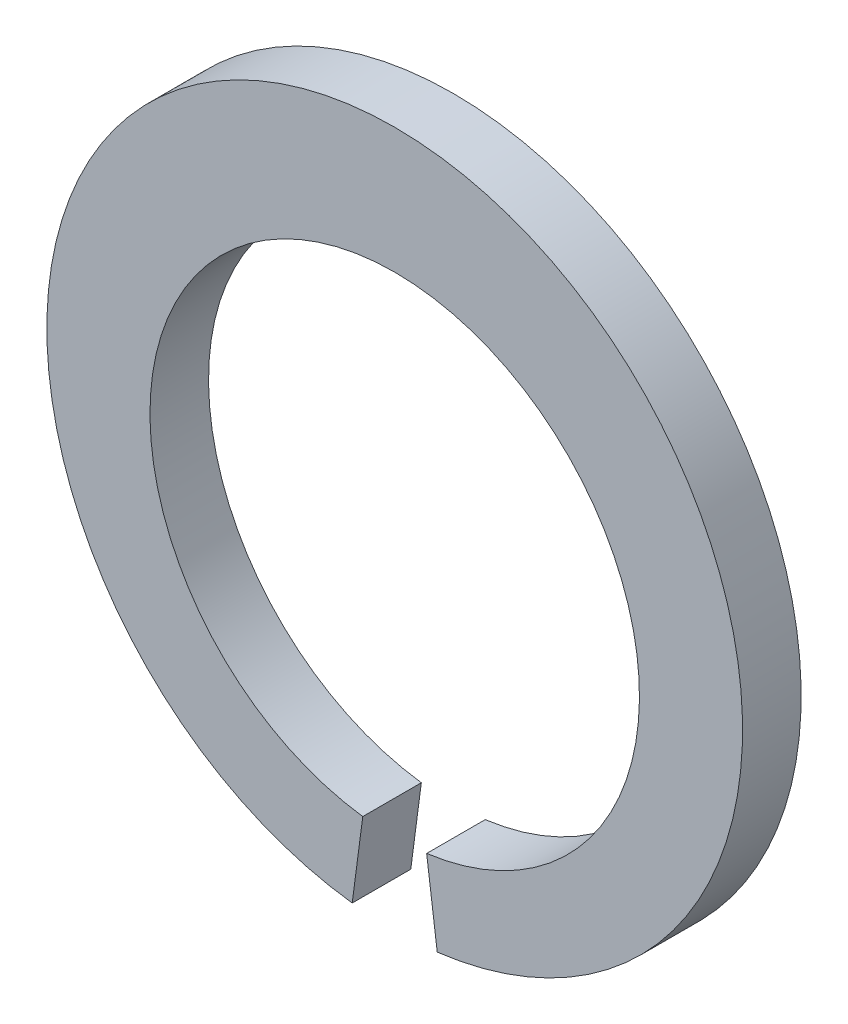
SolidWorks part; units mm, degrees
ref_plane "Plane1" through (0, 0, 0) normal (0, 0, 1) x (1, 0, 0)
ref_plane "Plane2" through (0, 0, 0) normal (0, 1, 0) x (1, 0, 0)
ref_plane "Plane3" through (0, 0, 0) normal (1, 0, 0) x (0, 0, -1)
sketch "Clipboard" plane through (0, 0, 0) normal (0, 0, 1) x (1, 0, 0)
  line L0 (0, 0) -> (2.286, 0)
  line L1 (0, 0) -> (0, 1.4732)
  circle A1 centre (0, 0) radius 4.7625
  dimension "ShaftDia" = 9.525
  dimension "LargeSection" = 2.286
  dimension "SmallSection" = 1.4732
sketch "BodySke" plane through (0, 0, 0) normal (0, 0, 1) x (1, 0, 0)
  line L0 (-1.5431, 0) -> (1.5431, 0) construction
  line L1 (0, 0) -> (0, 6.7437) construction
  line L2 (0.5818, -4.4196) -> (0.7741, -5.8802)
  line L3 (-0.5818, -4.4196) -> (-0.7741, -5.8802)
  line L4 (0, 0) -> (0.5818, -4.4196) construction
  line L5 (0, 0) -> (-0.5818, -4.4196) construction
  arc A2 (0.7741, -5.8802) -> (-0.7741, -5.8802) centre (0, 0.408) ccw construction
  arc A3 (0.5818, -4.4196) -> (-0.5818, -4.4196) centre (0, 0) ccw
  arc A7 (0.7741, -5.8802) -> (-0.7741, -5.8802) centre (0, 0.408) ccw
  dimension "GrooveDia" = 8.9154
  dimension "LargeRad" = 6.7437
  dimension "SmallRad" = 5.9309
  dimension "GapAngle" = 15
extrude "Body" add sketch "BodySke" against normal blind 1.0668
equation "' \"ShaftDia@Clipboard\" = 0.101"
equation "' \"Thickness@Body\" = 0.02"
equation "' \"GrooveDia@BodySke\" = 0.093"
equation "' \"LargeSection@Clipboard\" = 0.027"
equation "' \"SmallSection@Clipboard\" = 0.017"
equation "' \"ShaftDia@Clipboard\" = 0.375"
equation "' \"Thickness@Body\" = 0.042"
equation "' \"GrooveDia@BodySke\" = 0.351"
equation "' \"LargeSection@Clipboard\" = 0.09"
equation "' \"SmallSection@Clipboard\" = 0.058"
equation "\"LargeRad@BodySke\" =  \"GrooveDia@BodySke\" / 2 +  \"LargeSection@Clipboard\""
equation "\"SmallRad@BodySke\" =  \"GrooveDia@BodySke\" / 2 +  \"SmallSection@Clipboard\""
